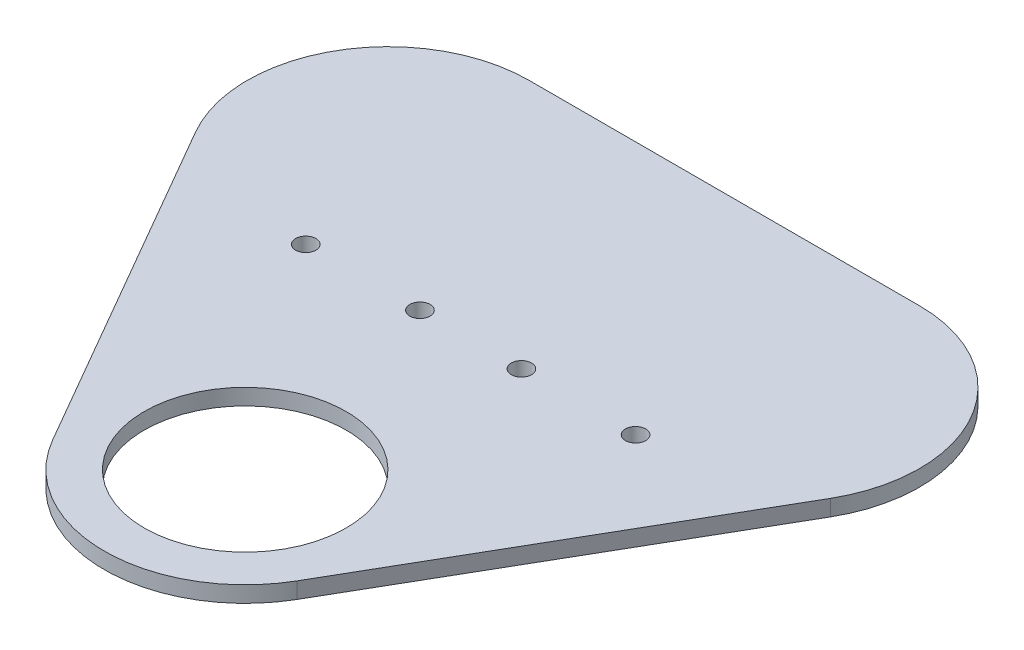
SolidWorks part; units mm, degrees
ref_plane "Front Plane" through (0, 0, 0) normal (0, 0, 1) x (1, 0, 0)
ref_plane "Top Plane" through (0, 0, 0) normal (0, 1, 0) x (1, 0, 0)
ref_plane "Right Plane" through (0, 0, 0) normal (1, 0, 0) x (0, 0, -1)
sketch "Sketch1" plane through (0, 0, 0) normal (0, 1, 0) x (1, 0, 0)
  line L0 (0, -94.9451) -> (-86.6025, 55.0549)
  line L1 (-86.6025, 55.0549) -> (86.6025, 55.0549)
  line L2 (86.6025, 55.0549) -> (0, -94.9451)
  point P2 (0, 55.0549)
  dimension "D1" = 150
extrude "Boss-Extrude1" add sketch "Sketch1" along normal blind 3.175
fillet "Fillet1" radius 27.78 3 edges at (86.6025, 1.5875, -55.0549) (-86.6025, 1.5875, -55.0549) (0, 1.5875, 94.9451)
sketch "Sketch2" plane through (0, 3.175, 0) normal (0, 1, 0) x (1, 0, 0)
  circle A0 centre (0, -39.3851) radius 19.9
  arc A2 (-24.0582, -53.2751) -> (24.0582, -53.2751) centre (0, -39.3851) ccw construction
  dimension "D1" = 39.8
sketch "Sketch5" plane through (0, 3.175, 0) normal (0, 1, 0) x (1, 0, 0)
  line L0 (32.5, 5.0549) -> (-32.5, 5.0549) construction
  line L1 (-10, 5.0549) -> (10, 5.0549) construction
  line L2 (38.4862, 55.0549) -> (-38.4862, 55.0549) construction
  circle A0 centre (32.5, 5.0549) radius 2
  circle A1 centre (-32.5, 5.0549) radius 2
  circle A4 centre (-10, 5.0549) radius 2
  circle A5 centre (10, 5.0549) radius 2
  point P4 (0, 5.0549)
  point P13 (0, 5.0549)
  dimension "D2" = 4
  dimension "D1" = 50
  dimension "D3" = 65
  dimension "D4" = 20
extrude "Cut-Extrude2" cut sketch "Sketch5" against normal through all
sketch "Sketch7" plane through (0, 3.175, 0) normal (0, 1, 0) x (1, 0, 0)
  line L0 (-7.3612, -43.6351) -> (0, -30.8851) construction
  line L1 (0, -30.8851) -> (7.3612, -43.6351) construction
  line L2 (7.3612, -43.6351) -> (-7.3612, -43.6351) construction
  line L3 (-7.3612, -43.6351) -> (3.6806, -37.2601) construction
  line L4 (-3.6806, -37.2601) -> (7.3612, -43.6351) construction
  circle A0 centre (0, -30.8851) radius 1.5
  circle A1 centre (-7.3612, -43.6351) radius 1.5
  circle A2 centre (7.3612, -43.6351) radius 1.5
  circle A3 centre (0, -39.3851) radius 10
  circle A5 centre (0, -39.3851) radius 3.925
  point P9 (0, -39.3851)
  dimension "D1" = 3
  dimension "D2" = 20
  dimension "D3" = 7.85
extrude "Cut-Extrude3" cut sketch "Sketch7" against normal blind 10 contours A0 | A1 | A5 | A2
extrude "Cut-Extrude4" cut sketch "Sketch2" against normal through all
